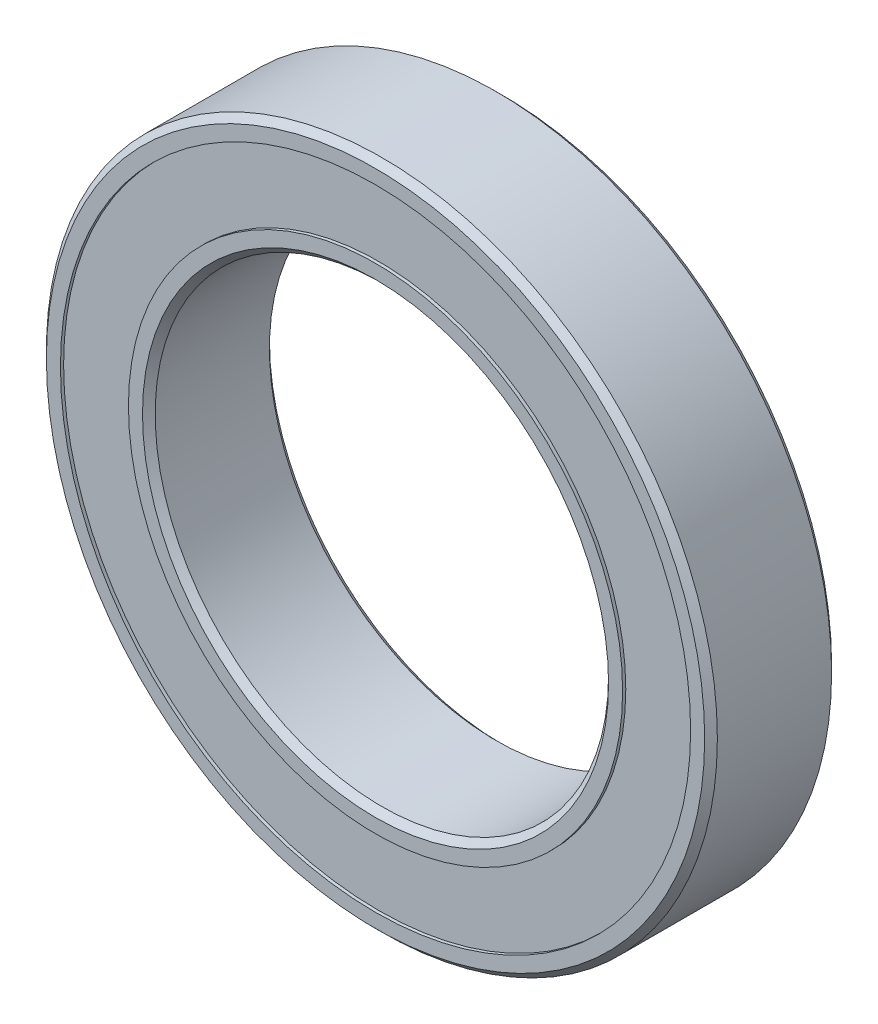
SolidWorks part; units mm, degrees
ref_plane "Front Plane" through (0, 0, 0) normal (0, 0, 1) x (1, 0, 0)
ref_plane "Top Plane" through (0, 0, 0) normal (0, 1, 0) x (1, 0, 0)
ref_plane "Right Plane" through (0, 0, 0) normal (1, 0, 0) x (0, 0, -1)
sketch "Sketch1" plane through (0, 0, 0) normal (0, 0, 1) x (1, 0, 0)
  circle A0 centre (0, 0) radius 18.5 construction
  circle A1 centre (0, 0) radius 12.5 construction
  dimension "OD" = 37
  dimension "ID" = 25
sketch "Sketch2" plane through (0, 0, 0) normal (1, 0, 0) x (0, 0, -1)
  line L0 (-3.5, 0) -> (3.5, 0) construction
  line L1 (0, 18.5) -> (0, -18.5) construction
  line L2 (3.15, 18.5) -> (-3.15, 18.5) construction
  line L3 (-3.15, 18.5) -> (-3.5, 18.15) construction
  line L4 (-3.5, 18.15) -> (-3.5, 17.375) construction
  line L5 (-3.5, 17.375) -> (-1.5556, 17.375) construction
  line L6 (3.5, 17.375) -> (1.5556, 17.375) construction
  line L7 (3.5, 18.15) -> (3.5, 17.375) construction
  line L8 (3.15, 18.5) -> (3.5, 18.15) construction
  line L9 (0, 18.5) -> (0, 15.5) construction
  line L10 (0, 15.5) -> (0, 12.5) construction
  line L11 (3.5, 15.5) -> (-3.5, 15.5) construction
  line L12 (-3.5, 12.85) -> (-3.5, 13.625) construction
  line L13 (-3.15, 12.5) -> (-3.5, 12.85) construction
  line L14 (3.15, 12.5) -> (-3.15, 12.5) construction
  line L15 (3.15, 12.5) -> (3.5, 12.85) construction
  line L16 (3.5, 12.85) -> (3.5, 13.625) construction
  line L17 (3.5, 13.625) -> (1.5556, 13.625) construction
  line L18 (-3.5, 13.625) -> (-1.5556, 13.625) construction
  line L19 (-3.5, 12.5) -> (-3.5, -12.5) construction
  line L20 (3.5, 18.5) -> (3.5, -18.5) construction
  arc A0 (-1.5556, 17.375) -> (1.5556, 17.375) centre (0, 15.5) cw construction
  arc A1 (-1.5556, 13.625) -> (1.5556, 13.625) centre (0, 15.5) ccw construction
  point P14 (0, 12.5)
  point P18 (0, 15.5)
  dimension "Approx. Ball Dia." = 4.8725
  dimension "D1" = 45
  dimension "D2" = 0.35
  dimension "D3" = 3.1111
  dimension "D4" = 1.875
  dimension "Width" = 7
  dimension "For Shaft Diameter" = 25
  dimension "For Housing ID" = 37
sketch "Sketch3" plane through (0, 0, 0) normal (1, 0, 0) x (0, 0, -1)
  line L0 (-3.5, 18.15) -> (-3.5, 17.375) construction
  line L1 (-3.15, 18.5) -> (-3.5, 18.15) construction
  line L2 (3.15, 18.5) -> (-3.15, 18.5) construction
  line L3 (3.15, 18.5) -> (3.5, 18.15) construction
  line L4 (3.5, 18.15) -> (3.5, 17.375) construction
  line L5 (3.5, 17.375) -> (1.5556, 17.375) construction
  line L6 (-3.5, 17.375) -> (-1.5556, 17.375) construction
  line L7 (-3.5, 18.15) -> (-3.5, 17.375)
  line L8 (-3.15, 18.5) -> (-3.5, 18.15)
  line L9 (3.15, 18.5) -> (-3.15, 18.5)
  line L10 (3.15, 18.5) -> (3.5, 18.15)
  line L11 (3.5, 18.15) -> (3.5, 17.375)
  line L12 (3.5, 17.375) -> (1.5556, 17.375)
  line L13 (-3.5, 17.375) -> (-1.5556, 17.375)
  line L14 (-3.5, 12.85) -> (-3.5, 13.625) construction
  line L15 (-3.15, 12.5) -> (-3.5, 12.85) construction
  line L16 (3.15, 12.5) -> (-3.15, 12.5) construction
  line L17 (3.15, 12.5) -> (3.5, 12.85) construction
  line L18 (3.5, 12.85) -> (3.5, 13.625) construction
  line L19 (3.5, 13.625) -> (1.5556, 13.625) construction
  line L20 (-3.5, 13.625) -> (-1.5556, 13.625) construction
  line L21 (-3.5, 12.85) -> (-3.5, 13.625)
  line L22 (-3.15, 12.5) -> (-3.5, 12.85)
  line L23 (3.15, 12.5) -> (-3.15, 12.5)
  line L24 (3.15, 12.5) -> (3.5, 12.85)
  line L25 (3.5, 12.85) -> (3.5, 13.625)
  line L26 (3.5, 13.625) -> (1.5556, 13.625)
  line L27 (-3.5, 13.625) -> (-1.5556, 13.625)
  arc A0 (1.5556, 17.375) -> (-1.5556, 17.375) centre (0, 15.5) ccw construction
  arc A1 (1.5556, 17.375) -> (-1.5556, 17.375) centre (0, 15.5) ccw
  arc A2 (-1.5556, 13.625) -> (1.5556, 13.625) centre (0, 15.5) ccw construction
  arc A3 (-1.5556, 13.625) -> (1.5556, 13.625) centre (0, 15.5) ccw
revolve "Revolve1" add sketch "Sketch3" angle 360 about L0
sketch "Sketch4" plane through (0, 0, 0) normal (1, 0, 0) x (0, 0, -1)
  line L0 (-2.4363, 15.5) -> (2.4363, 15.5)
  arc A2 (-2.4363, 15.5) -> (2.4363, 15.5) centre (0, 15.5) cw
  arc A3 (1.5556, 17.375) -> (-1.5556, 17.375) centre (0, 15.5) ccw construction
revolve "Revolve2" add sketch "Sketch4" angle 360 about L0
pattern_circular "CirPattern1" count 12 over 360 about axis through (0, 0, 0) along (0, 0, 1) of bodies 104
sketch "Sketch5" plane through (0, 0, 0) normal (1, 0, 0) x (0, 0, -1)
  line L0 (-3.5, 17.375) -> (-1.5556, 17.375) construction
  line L1 (-3.325, 17.375) -> (-2.4363, 17.375)
  line L2 (-3.325, 17.375) -> (-3.325, 13.625)
  line L3 (-3.325, 13.625) -> (-2.4363, 13.625)
  line L4 (-2.4363, 17.375) -> (-2.4363, 13.625)
  line L6 (3.5, 17.375) -> (1.5556, 17.375) construction
  line L7 (3.325, 17.375) -> (2.4363, 17.375)
  line L8 (3.325, 17.375) -> (3.325, 13.625)
  line L9 (3.325, 13.625) -> (2.4363, 13.625)
  line L10 (2.4363, 17.375) -> (2.4363, 13.625)
  line L12 (-3.15, 18.5) -> (-3.5, 18.15) construction
  line L13 (-3.5, 13.625) -> (-1.5556, 13.625) construction
  line L14 (3.5, 13.625) -> (1.5556, 13.625) construction
  point P18 (-3.325, 18.325)
revolve "Revolve3" add sketch "Sketch5" angle 360 about L0
equation "\"D2@Sketch2\"= \"Width@Sketch2\" * .05"
equation "\"D3@Sketch2\"=\"Width@Sketch2\" / 2.25"
equation "\"D4@Sketch2\"=( \"OD@Sketch1\" - \"Width@Sketch2\" ) *.5 *.125"
equation "\"Approx. No. of Balls\"= ( pi * \"OD@Sketch1\" ) * .5 / \"Approx. Ball Dia.@Sketch2\""
equation "\"Balls@CirPattern1\"=\"Approx. No. of Balls\""
